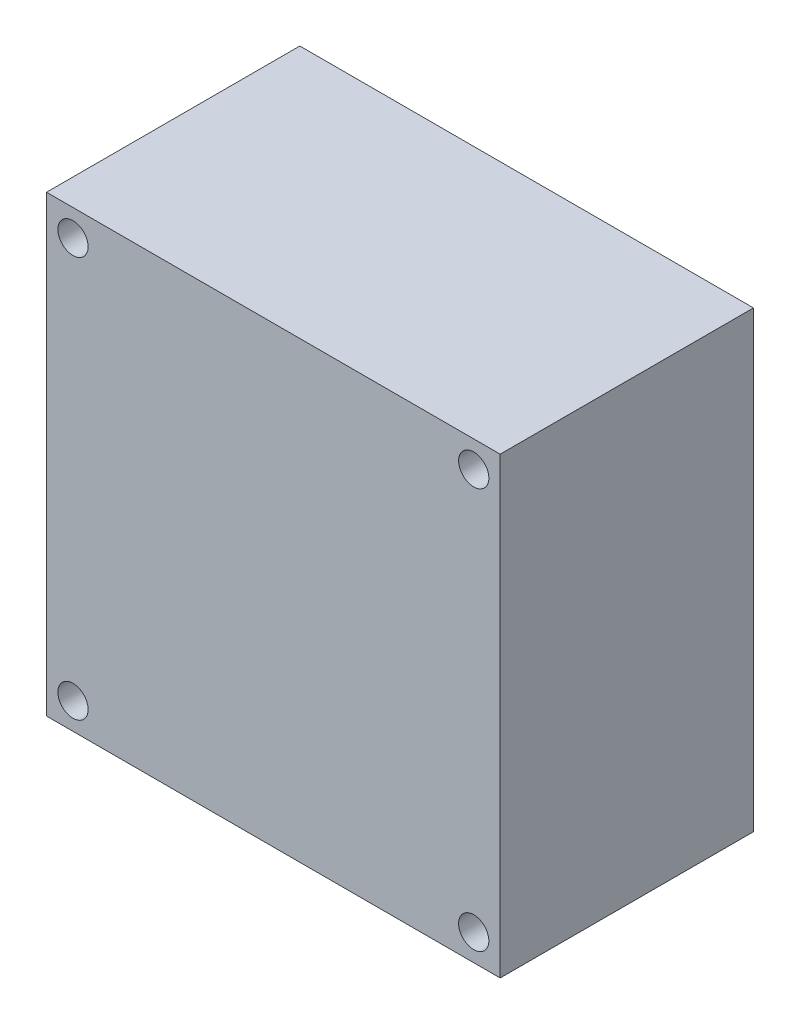
SolidWorks part; units mm, degrees
ref_plane "Płaszczyzna przednia" through (0, 0, 0) normal (0, 0, 1) x (1, 0, 0)
ref_plane "Płaszczyzna górna" through (0, 0, 0) normal (0, 1, 0) x (1, 0, 0)
ref_plane "Płaszczyzna prawa" through (0, 0, 0) normal (1, 0, 0) x (0, 0, -1)
sketch "Szkic1" plane through (0, 0, 0) normal (0, 0, 1) x (1, 0, 0)
  line L1 (0, 0) -> (120, 0)
  line L2 (0, 0) -> (0, 120)
  line L3 (0, 120) -> (120, 120)
  line L4 (120, 0) -> (120, 120)
  dimension "D1" = 120
  dimension "D2" = 120
extrude "Dodanie-wyciągnięcie1" add sketch "Szkic1" along normal blind 67
sketch "Szkic5" plane through (0, 0, 67) normal (0, 0, 1) x (1, 0, 0)
  line L0 (60, 120) -> (60, 0) construction
  line L1 (120, 120) -> (0, 120) construction
  line L2 (0, 0) -> (120, 0) construction
  line L3 (0, 120) -> (0, 0) construction
  circle A0 centre (7, 113) radius 4
  circle A1 centre (7, 7) radius 4
  circle A2 centre (113, 113) radius 4
  circle A3 centre (113, 7) radius 4
  dimension "D1" = 8
  dimension "D2" = 7
  dimension "D3" = 7
  dimension "D4" = 7
  dimension "D5" = 8
  dimension "D6" = 7
extrude "Wytnij-wyciągnięcie1" cut sketch "Szkic5" against normal blind 25
